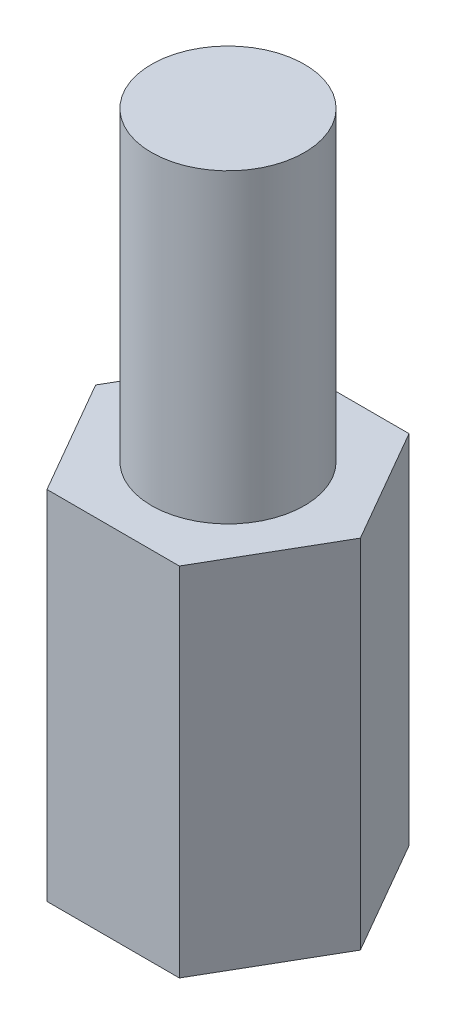
SolidWorks part; units mm, degrees
ref_plane "Спереди" through (0, 0, 0) normal (0, 0, 1) x (1, 0, 0)
ref_plane "Сверху" through (0, 0, 0) normal (0, 1, 0) x (1, 0, 0)
ref_plane "Справа" through (0, 0, 0) normal (1, 0, 0) x (0, 0, -1)
sketch "Эскиз1" plane through (0, 0, 0) normal (0, 1, 0) x (1, 0, 0)
  line L4 (-1.3017, -2.25) -> (1.2977, -2.2523)
  line L5 (1.2977, -2.2523) -> (2.5994, -0.0023)
  line L6 (2.5994, -0.0023) -> (1.3017, 2.25)
  line L7 (1.3017, 2.25) -> (-1.2977, 2.2523)
  line L8 (-1.2977, 2.2523) -> (-2.5994, 0.0023)
  line L9 (-2.5994, 0.0023) -> (-1.3017, -2.25)
extrude "Бобышка-Вытянуть1" add sketch "Эскиз1" along normal blind 7 contours L4 L5 L6 L7 L8 L9
sketch "Эскиз2" plane through (0, 0, 0) normal (0, -1, 0) x (1, 0, 0)
  circle A0 centre (0, 0) radius 1.25
extrude "Вырез-Вытянуть1" cut sketch "Эскиз2" against normal blind 6.5 contours A0
cosmetic thread "Условное изображение резьбы2" parameters "D1"=6, "D2"=3
sketch "Эскиз3" plane through (0, 7, 0) normal (0, 1, 0) x (1, 0, 0)
  circle A0 centre (0, 0) radius 1.5
extrude "Бобышка-Вытянуть2" add sketch "Эскиз3" along normal blind 6 separate body
cosmetic thread "Условное изображение резьбы1" parameters "D2"=2.439
cosmetic thread "Условное изображение резьбы3" parameters "D2"=2.439
